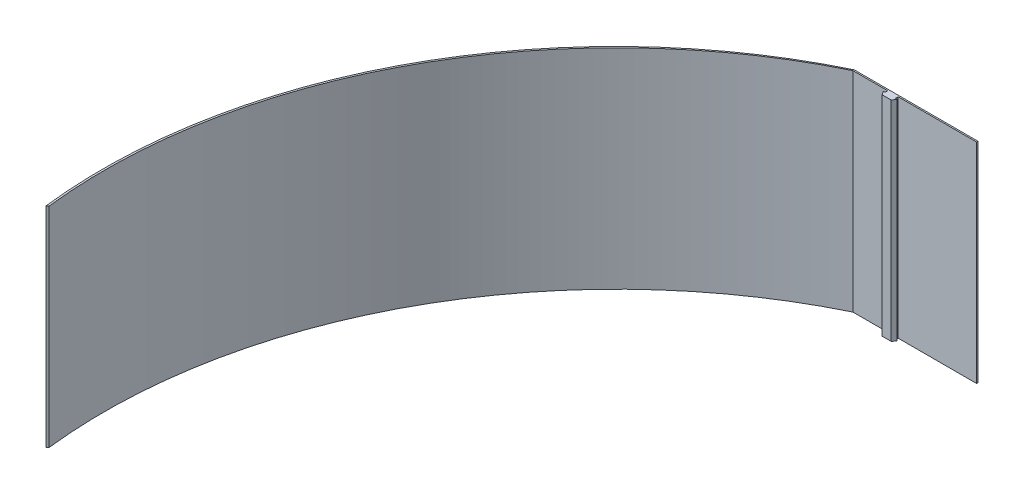
SolidWorks part; units mm, degrees
ref_plane "Front Plane" through (0, 0, 0) normal (0, 0, 1) x (1, 0, 0)
ref_plane "Top Plane" through (0, 0, 0) normal (0, 1, 0) x (1, 0, 0)
ref_plane "Right Plane" through (0, 0, 0) normal (1, 0, 0) x (0, 0, -1)
sketch "Sketch1" plane through (0, 0, 0) normal (0, 1, 0) x (1, 0, 0)
  line L1 (-3, 0) -> (-3, -1.6)
  line L2 (-3, -1.6) -> (-4, -1.6)
  line L3 (-4, -1.6) -> (-2.5996, -3.6)
  line L4 (-2.5996, -3.6) -> (2.5996, -3.6)
  line L5 (2.5996, -3.6) -> (4, -1.6)
  line L6 (4, -1.6) -> (3, -1.6)
  line L7 (3, -1.6) -> (3, 0)
  line L9 (-3, 0) -> (-23, 0)
  line L13 (48, 0) -> (3, 0)
  line L14 (0, -4.9469) -> (0, 4.9469) construction
  line L16 (-23, 0.8) -> (48, 0.8)
  line L17 (48, 0.8) -> (48, 0)
  line L18 (-187.3173, -298.721) -> (-186.3191, -297.9482)
  arc A3 (-23, 0) -> (-186.3191, -297.9482) centre (105.6341, -264.2457) ccw
  arc A4 (-23, 0.8) -> (-187.3173, -298.721) centre (104.8382, -264.1648) ccw
  point P4 (0, 0)
  point P7 (0, 0)
  dimension "D11" = 0.8
  dimension "D12" = 0.8
  dimension "D1" = 20
  dimension "D2" = 3
  dimension "D3" = 3
  dimension "D4" = 1
  dimension "D5" = 1
  dimension "D6" = 125
  dimension "D7" = 1.6
  dimension "D8" = 2
  dimension "D9" = 125
  dimension "D10" = 45
extrude "Boss-Extrude1" add sketch "Sketch1" along normal blind 120
